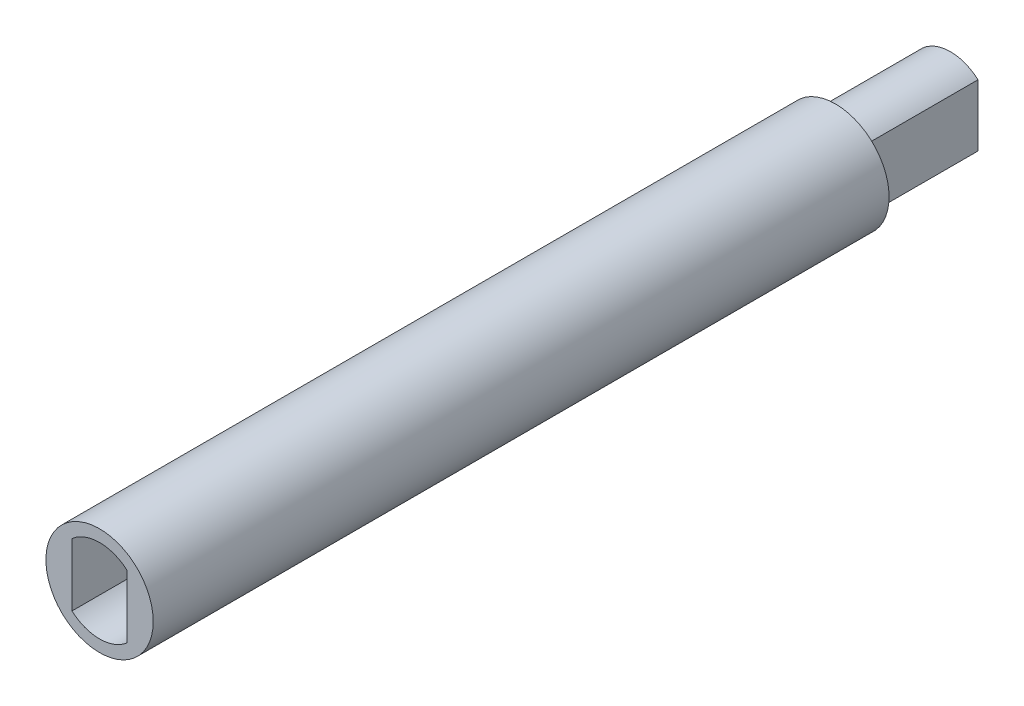
SolidWorks part; units mm, degrees
ref_plane "Alzado" through (0, 0, 0) normal (0, 0, 1) x (1, 0, 0)
ref_plane "Planta" through (0, 0, 0) normal (0, 1, 0) x (1, 0, 0)
ref_plane "Vista lateral" through (0, 0, 0) normal (1, 0, 0) x (0, 0, -1)
sketch "Croquis1" plane through (0, 0, 0) normal (0, 0, 1) x (1, 0, 0)
  circle A0 centre (0, 0) radius 3.5
  dimension "D1" = 7
extrude "Saliente-Extruir1" add sketch "Croquis1" against normal blind 65.5
sketch "Croquis6" plane through (0, 0, 0) normal (0, 0, 1) x (1, 0, 0)
  line L0 (0, 0) -> (-1.8, 0) construction
  line L1 (-1.8, 0) -> (0, 0) construction
  line L2 (0, 0) -> (0, 0.6701) construction
  line L3 (-1.8, 2.0459) -> (-1.8, -2.0459)
  line L4 (1.8, 2.0459) -> (1.8, -2.0459)
  arc A1 (-1.8, -2.0459) -> (1.8, -2.0459) centre (0, 0) ccw
  arc A2 (1.8, 2.0459) -> (-1.8, 2.0459) centre (0, 0) ccw
  point P9 (-1.8, 0)
  dimension "D2" = 5.45
  dimension "D1" = 1.8
  dimension "D3" = 1.8
extrude "Cortar-Extruir3" cut sketch "Croquis6" against normal blind 8
sketch "Croquis7" plane through (0, 0, -65.5) normal (0, 0, -1) x (-1, 0, 0)
  line L0 (0, 0.6984) -> (0, 0) construction
  line L1 (0, 0) -> (-1.8, 0) construction
  line L2 (-1.8, 2.0125) -> (-1.8, -2.0125)
  line L3 (1.8, 2.0125) -> (1.8, -2.0125)
  arc A0 (-1.8, -2.0125) -> (1.8, -2.0125) centre (0, 0) ccw
  arc A1 (1.8, 2.0125) -> (-1.8, 2.0125) centre (0, 0) ccw
  point P8 (-1.8, 0)
  circle M7 centre (0, 0) radius 3.5
  dimension "D1" = 5.4
  dimension "D2" = 1.8
extrude "Cortar-Extruir5" cut sketch "Croquis7" against normal blind 20 contours A1 L3 A0 L2 M7
sketch "Croquis8" plane through (-1.8, 0, 0) normal (-1, 0, 0) x (0, 0, 1)
  line L0 (-45.5, -0.4367) -> (-53, -0.4367) construction
  line L1 (-45.5, 2.0125) -> (-45.5, -2.0125) construction
  line L2 (-53, 4.2047) -> (-53, -5.0782)
  line L3 (-53, -5.0782) -> (-65.6172, -5.0782)
  line L4 (-65.6172, 4.2047) -> (-53, 4.2047)
  line L5 (-65.6172, 4.2047) -> (-65.6172, -5.0782)
  point P7 (-53, -0.4367)
  dimension "D1" = 7.5
extrude "Cortar-Extruir6" cut sketch "Croquis8" against normal blind 10
sketch "Croquis10" plane through (0, 0, 0) normal (0, 0, 1) x (1, 0, 0)
  line L0 (-1.8, 2.0459) -> (-1.8, -2.0459)
  line L1 (1.8, 2.0459) -> (1.8, -2.0459)
  circle A0 centre (0, 0) radius 3.5
  arc A1 (-1.8, -2.0459) -> (1.8, -2.0459) centre (0, 0) ccw
  arc A2 (1.8, 2.0459) -> (-1.8, 2.0459) centre (0, 0) ccw
extrude "Saliente-Extruir2" add sketch "Croquis10" along normal blind 2.5
